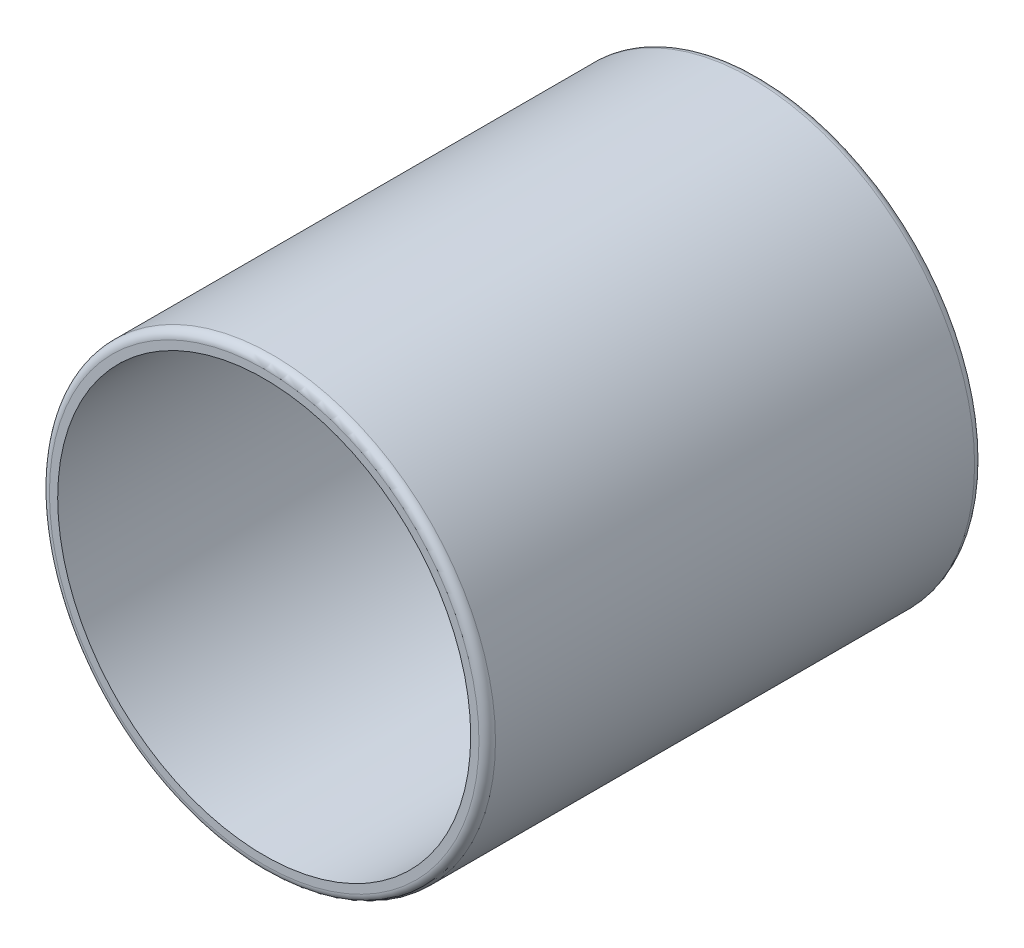
SolidWorks part; units mm, degrees
ref_plane "Front" through (0, 0, 0) normal (0, 0, 1) x (1, 0, 0)
ref_plane "Top" through (0, 0, 0) normal (0, 1, 0) x (1, 0, 0)
ref_plane "Right" through (0, 0, 0) normal (1, 0, 0) x (0, 0, -1)
sketch "Sketch1" plane through (0, 0, 0) normal (0, 0, 1) x (1, 0, 0)
  circle A0 centre (0, 0) radius 250
  dimension "D1" = 500
extrude "Extrude-Thin1" add sketch "Sketch1" along normal blind 600 thin
fillet "Fillet1" radius 10 2 edges at (270, 0, 0) (270, 0, 600)
